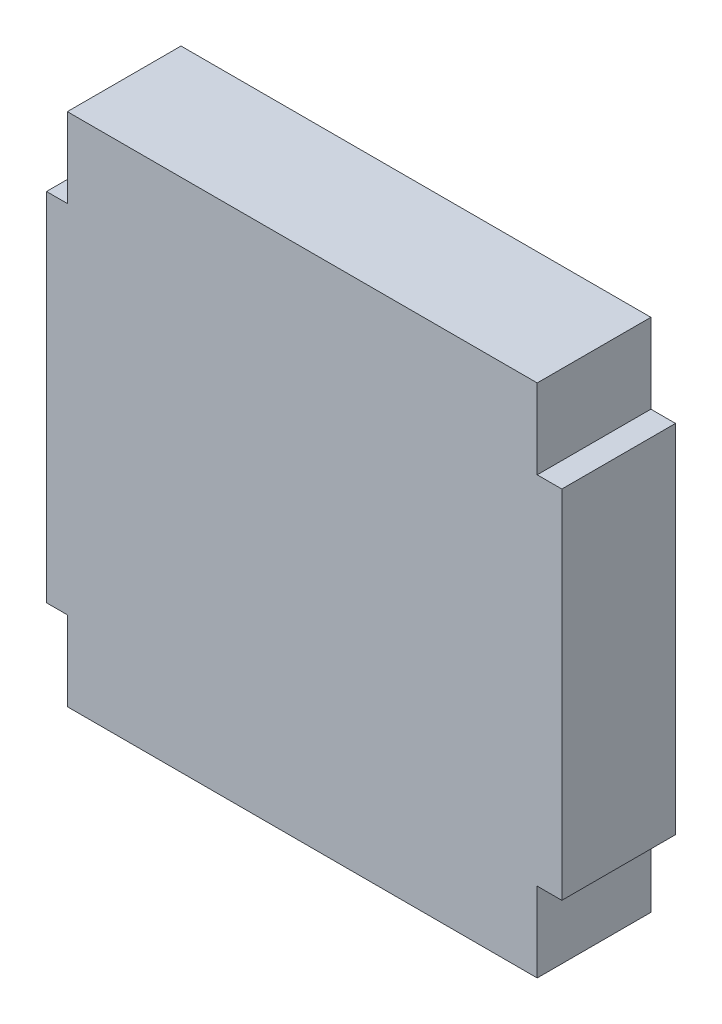
SolidWorks part; units mm, degrees
ref_plane "前视基准面" through (0, 0, 0) normal (0, 0, 1) x (1, 0, 0)
ref_plane "上视基准面" through (0, 0, 0) normal (0, 1, 0) x (1, 0, 0)
ref_plane "右视基准面" through (0, 0, 0) normal (1, 0, 0) x (0, 0, -1)
sketch "草图1" plane through (0, 0, 0) normal (0, 0, 1) x (1, 0, 0)
  line L0 (3.1, 3.4) -> (3.1, 2.35)
  line L1 (3.1, 2.35) -> (3.425, 2.35)
  line L2 (3.425, 2.35) -> (3.425, -2.35)
  line L3 (3.425, -2.35) -> (3.1, -2.35)
  line L4 (3.1, -2.35) -> (3.1, -3.4)
  line L5 (3.1, -3.4) -> (-3.1, -3.4)
  line L6 (-3.1, -3.4) -> (-3.1, -2.35)
  line L7 (-3.1, -2.35) -> (-3.375, -2.35)
  line L8 (-3.375, -2.35) -> (-3.375, 2.35)
  line L9 (-3.375, 2.35) -> (-3.1, 2.35)
  line L10 (-3.1, 2.35) -> (-3.1, 3.4)
  line L11 (-3.1, 3.4) -> (3.1, 3.4)
extrude "Component_Outline" add sketch "草图1" along normal blind 1.5 separate body
sketch3d "3D草图1"
  line L0 (0, 0, 0) -> (1, 0, 0)
  line L1 (0, 0, 0) -> (0, 1, 0)
  line L2 (0, 0, 0) -> (0, 0, 1)
  point P0 (0, 0, 0)
